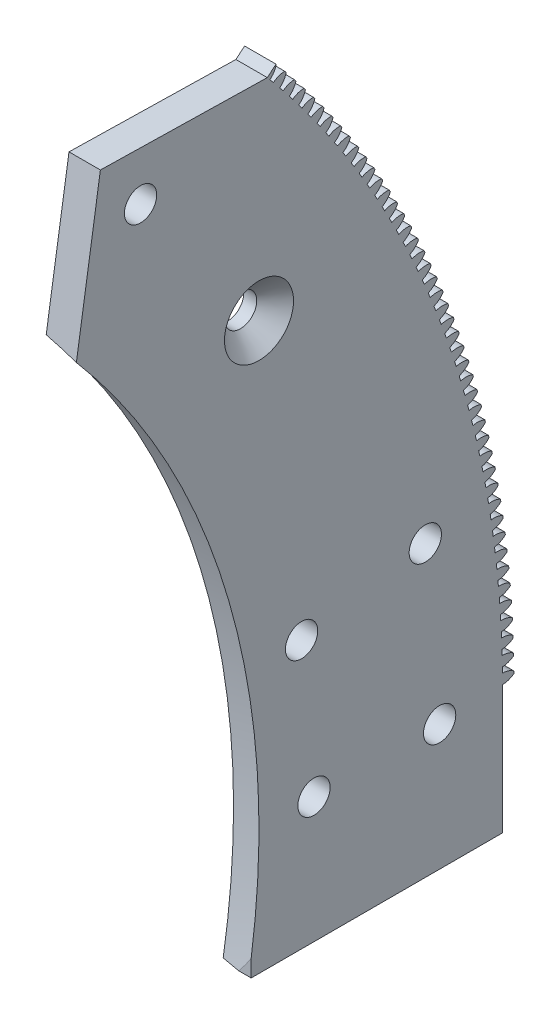
SolidWorks part; units mm, degrees
material "ABS"
ref_plane "Front Plane" through (0, 0, 0) normal (0, 0, 1) x (1, 0, 0)
ref_plane "Top Plane" through (0, 0, 0) normal (0, 1, 0) x (1, 0, 0)
ref_plane "Right Plane" through (0, 0, 0) normal (1, 0, 0) x (0, 0, -1)
ref_plane "Plane2" through (6.35, 0, 0) normal (1, 0, 0) x (0, 0, -1)
sketch "Sketch1" plane through (0, 0, 0) normal (1, 0, 0) x (0, 0, -1)
  line L0 (-1000, 0) -> (152.4, 0) construction
  line L1 (152.4, 0) -> (152.4, -25.4)
  line L2 (0, 0) -> (116.7452, 97.9608) construction
  line L4 (203.2, 0) -> (49000, 0) construction
  line L7 (152.4, -25.4) -> (203.2, -25.4)
  line L8 (203.2, 0) -> (203.2, -25.4)
  line L10 (-19.9245, -15.6845) -> (159.6649, 125.6875) construction
  line L61 (160.8976, 124.1056) -> (0, 0) construction
  line L62 (136.2027, 114.2876) -> (121.9167, 131.313) construction
  line L63 (116.7452, 97.9608) -> (121.9167, 131.313)
  line L67 (121.9167, 131.313) -> (155.6602, 130.6144)
  line L68 (0, 0) -> (35966.99, 34732.9185) construction
  line L69 (159.6736, 125.6943) -> (159.6985, 125.714) construction
  arc A2 (152.4, 0) -> (116.7452, 97.9608) centre (0, 0) ccw
  circle A19 centre (0, 0) radius 203.2 construction
  arc A22 (155.6602, 130.6144) -> (203.2, 0) centre (0, 0) cw
  point P6 (159.6985, 125.714)
  point P7 (116.7452, 97.9608)
  dimension "D1" = 152.4
  dimension "D2" = 6.35
  dimension "D12" = 406.4
  dimension "D3" = 40
  dimension "D4" = 50.8
  dimension "D5" = 25.4
  dimension "D11" = 22.225
  dimension "D13" = 44
sketch "Sketch2" plane through (6.35, 0, 0) normal (1, 0, 0) x (0, 0, -1)
  line L0 (0, 0) -> (165.1, 0) construction
  line L1 (165.1, 0) -> (190.5, 0) construction
  line L2 (0, 0) -> (49240.3877, 8682.4089) construction
  circle A0 centre (165.1, 0) radius 3.2639
  circle A1 centre (190.5, 0) radius 3.2639
  arc A3 (165.1, 0) -> (162.5918, 28.6693) centre (0, 0) ccw construction
  circle A4 centre (162.5918, 28.6693) radius 3.2639
  arc A5 (190.5, 0) -> (187.6059, 33.08) centre (0, 0) ccw construction
  circle A6 centre (187.6059, 33.08) radius 3.2639
  dimension "D3" = 6.5278
  dimension "D4" = 6.5278
  dimension "D6" = 6.5278
  dimension "D7" = 6.5278
  dimension "D1" = 165.1
  dimension "D2" = 25.4
  dimension "D5" = 10
sketch "Sketch3" plane through (6.35, 0, 0) normal (1, 0, 0) x (0, 0, -1)
  line L0 (0, 0) -> (114.3, 0) construction
  line L1 (0, 0) -> (153.9793, 88.9) construction
  circle A0 centre (153.9793, 88.9) radius 3.2639
  dimension "D4" = 6.5278
  dimension "D1" = 114.3
  dimension "D2" = 30
  dimension "D3" = 177.8
sketch "Sketch11" plane through (6.35, 0, 0) normal (1, 0, 0) x (0, 0, -1)
  line L0 (-785.502, -659.1144) -> (0, 0) construction
  line L2 (-1000, 0) -> (0, 0) construction
  line L3 (203.2, 0) -> (205.5, 0)
  line L4 (155.6602, 130.6144) -> (157.4221, 132.0929)
  line L5 (157.4221, 132.0929) -> (921.7047, 773.4021) construction
  arc A0 (-230, 0) -> (-176.1902, -147.8412) centre (0, 0) ccw construction
  arc A1 (-205.5, 0) -> (-157.4221, -132.0929) centre (0, 0) ccw construction
  arc A2 (-203.1, 0) -> (-155.5836, -130.5502) centre (0, 0) ccw construction
  arc A3 (205.5, 0) -> (157.4221, 132.0929) centre (0, 0) ccw
  arc A4 (230, 0) -> (176.1902, 147.8412) centre (0, 0) ccw construction
  arc A5 (-203.1, 0) -> (-155.5836, -130.5502) centre (0, 0) ccw
  arc A6 (155.6602, 130.6144) -> (203.2, 0) centre (0, 0) cw
  dimension "D1" = 460
  dimension "D2" = 411
  dimension "D4" = 203.2
  dimension "D3" = 2.4
  dimension "D5" = 40
extrude "Boss-Extrude2" add sketch "Sketch11" against normal blind 6.35
sketch "Sketch12" plane through (6.35, 0, 0) normal (1, 0, 0) x (0, 0, -1)
  line L0 (0, 0) -> (205.5, 0) construction
  line L1 (203.2, 0) -> (205.5, 0) construction
  line L2 (204.4985, 0.7854) -> (204.4985, -0.7854) construction
  line L3 (0, 0) -> (203.1992, 0.5545) construction
  line L4 (202.3406, 0) -> (206.4945, 1.5119) construction
  line L5 (0, 0) -> (206.4939, 1.5861) construction
  line L6 (204.4985, 0.7854) -> (204.4864, 2.3561) construction
  circle A0 centre (0, 0) radius 204.5 construction
  arc A1 (205.5, 0) -> (157.4221, 132.0929) centre (0, 0) ccw construction
  circle A2 centre (0, 0) radius 203.2 construction
  arc A3 (203.1992, 0.5545) -> (206.4856, 2.4358) centre (203.1888, 4.3838) ccw
  arc A4 (206.5, 0) -> (206.4856, -2.4358) centre (0, 0) cw
  arc A5 (203.1992, -0.5545) -> (206.4856, -2.4358) centre (203.1888, -4.3838) cw
  arc A6 (206.5, 0) -> (158.1882, 132.7356) centre (0, 0) ccw
  arc A7 (206.5, 0) -> (206.4856, 2.4358) centre (0, 0) ccw
  arc A8 (203.1992, 0.5545) -> (203.1992, -0.5545) centre (0, 0) cw
  dimension "D1" = 409
  dimension "D5" = 406.4
  dimension "D3" = 20
  dimension "D4" = 0.44
  dimension "D2" = 1
extrude "Boss-Extrude3" add sketch "Sketch1" along normal blind 6.35
extrude "Cut-Extrude4" cut sketch "Sketch12" against normal blind 6.35
pattern_circular "CirPattern3" count 100 every 0.88 about axis through (0, 0, 0) along (1, 0, 0) of "Cut-Extrude4"
extrude "Cut-Extrude5" cut sketch "Sketch2" against normal blind 6.35
extrude "Cut-Extrude6" cut sketch "Sketch3" against normal blind 6.35
sketch "Sketch15" plane through (6.35, 0, 0) normal (1, 0, 0) x (0, 0, -1)
  line L0 (0, 0) -> (130.0347, 121.2593) construction
  line L1 (-196961.5506, -34729.6355) -> (246201.9383, 43412.0444) construction
  circle A0 centre (130.0347, 121.2593) radius 3.2639
  dimension "D3" = 6.5278
  dimension "D1" = 177.8
  dimension "D2" = 33
extrude "Cut-Extrude7" cut sketch "Sketch15" against normal through all
sketch "Sketch16" plane through (6.35, 0, 0) normal (1, 0, 0) x (0, 0, -1)
  line L0 (0, 0) -> (153.9793, 88.9) construction
sketch "Sketch17" plane through (0, 0, 0) normal (-1, 0, 0) x (0, 0, 1)
  line L0 (0, 0) -> (-153.9793, 88.9) construction
ref_plane "Plane1" through (0, 0, 0) normal (0, -0.866, -0.5) x (-1, 0, 0)
sketch "Sketch18" plane through (0, 0, 0) normal (0, -0.866, -0.5) x (-1, 0, 0)
  line L0 (0, 0) -> (-6.35, 0) construction
  line L1 (-6.35, 0) -> (-6.35, 142.9808) construction
  line L2 (-6.35, 177.8) -> (-6.35, 170.815) construction
  line L3 (-6.35, 177.8) -> (-6.35, 184.785)
  line L4 (-1006.35, 177.8) -> (48993.65, 177.8) construction
  line L5 (-6.35, 170.815) -> (0.635, 177.8) construction
  line L6 (0.635, 177.8) -> (-6.35, 184.785)
  line L7 (0.635, 177.8) -> (-6.35, 177.8)
  dimension "D1" = 6.985
  dimension "D2" = 6.985
  dimension "D3" = 90
revolve "Cut-Revolve3" cut sketch "Sketch18" angle 360 about L4
sketch "Sketch21" plane through (0, 0, 0) normal (0, 1, 0) x (1, 0, 0)
  line L0 (0, 0) -> (-19.05, 0) construction
  line L1 (12.7, 0) -> (12.7, 152.4)
  line L2 (0, 0) -> (12.7, 0) construction
  line L3 (-19.05, 0) -> (-19.05, 38.1) construction
  line L4 (-19.05, 38.1) -> (-137.6778, 38.1)
  line L5 (-19.05, 38.1) -> (99.5778, 38.1)
  line L6 (99.5778, 38.1) -> (-49900.4222, 38.1) construction
  line L7 (-1000, 0) -> (49000, 0) construction
  arc A0 (99.5778, 38.1) -> (-137.6778, 38.1) centre (-19.05, 38.1) ccw
  dimension "D3" = 12.7
  dimension "D1" = 19.05
  dimension "D2" = 152.4
  dimension "D4" = 38.1
revolve "Cut-Revolve7" cut sketch "Sketch21" angle 360 about L7
sketch "Sketch22" plane through (6.35, 0, 0) normal (1, 0, 0) x (0, 0, -1)
  line L0 (0, 0) -> (130.0347, 121.2593)
  line L1 (0, 0) -> (177.8, 0)
  dimension "D1" = 177.8
equation "\"Module\"= 1mm"
equation "\"Number of Teeth\"= 409"
equation "\"D1@Sketch12\"=\"Module\" * \"Number of Teeth\""
equation "\"D4@Sketch12\"=180 / \"Number of Teeth\""
equation "\"D2\"= 360 / \"Number of Teeth\""
equation "\"D2@Sketch11\"=( \"Number of Teeth\" + 2) * \"Module\""
equation "\"D2@CirPattern3\"= 360 / \"Number of Teeth\""
